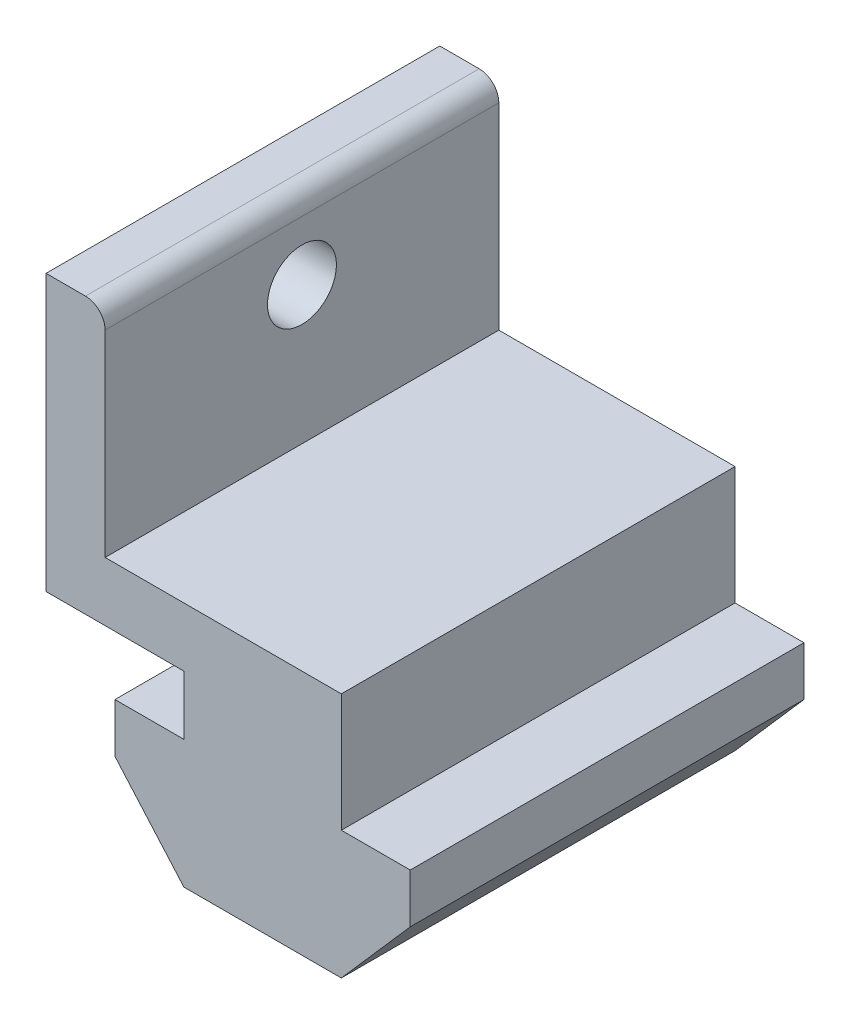
SolidWorks part; units mm, degrees
ref_plane "Piano frontale" through (0, 0, 0) normal (0, 0, 1) x (1, 0, 0)
ref_plane "Piano superiore" through (0, 0, 0) normal (0, 1, 0) x (1, 0, 0)
ref_plane "Piano destro" through (0, 0, 0) normal (1, 0, 0) x (0, 0, -1)
sketch "Schizzo2" plane through (0, 0, 0) normal (0, 0, 1) x (1, 0, 0)
  line L0 (0, 0) -> (0, 12.9875) construction
  line L1 (-4, 9.5) -> (-11, 9.5)
  line L2 (-11, 9.5) -> (-11, 23.5)
  line L3 (-11, 23.5) -> (-9, 23.5)
  line L4 (-8, 22.5) -> (-8, 12.5)
  line L5 (-8, 12.5) -> (4, 12.5)
  line L6 (4, 12.5) -> (4, 9.5)
  line L13 (-4, 0) -> (4, 0)
  line L14 (-7.5, 4) -> (-4, 0)
  line L15 (-7.5, 6.5) -> (-7.5, 4)
  line L16 (-4, 6.5) -> (-7.5, 6.5)
  line L17 (-4, 9.5) -> (-4, 6.5)
  line L44 (7.5, 4) -> (4, 0)
  line L45 (7.5, 6.5) -> (7.5, 4)
  line L46 (4, 6.5) -> (7.5, 6.5)
  line L72 (4, 9.5) -> (4, 6.5)
  arc A0 (-9, 23.5) -> (-8, 22.5) centre (-9, 22.5) cw
  point P9 (-8, 23.5)
  dimension "D11" = 1
  dimension "D1" = 8
  dimension "D2" = 4
  dimension "D3" = 2.5
  dimension "D4" = 8
  dimension "D5" = 3
  dimension "D6" = 15
  dimension "D7" = 11
  dimension "D8" = 3
  dimension "D9" = 3
  dimension "D10" = 14
extrude "Estrusione-Estrusione1" add sketch "Schizzo2" against normal blind 20
sketch "Schizzo6" plane through (-11, 0, 0) normal (-1, 0, 0) x (0, 0, 1)
  line L0 (0, 23.5) -> (0, 9.5) construction
  line L1 (-20, 23.5) -> (0, 23.5) construction
  circle A0 centre (-10, 19.5) radius 1.75
  dimension "D2" = 3.5
  dimension "D1" = 10
  dimension "D3" = 4
extrude "Taglio-Estrusione1" cut sketch "Schizzo6" against normal up to next
sketch "Schizzo11" plane through (0, 0, -20) normal (0, 0, -1) x (-1, 0, 0)
  line L0 (4, 0) -> (-4, 0) construction
  line L1 (7.5, 6.5) -> (7.5, 4) construction
  text T0 "3" font "Century Gothic" height 6.5
  dimension "D1" = 1
  dimension "D2" = 10.5
extrude "Estrusione-Estrusione4" add sketch "Schizzo11" along normal blind 0.6
